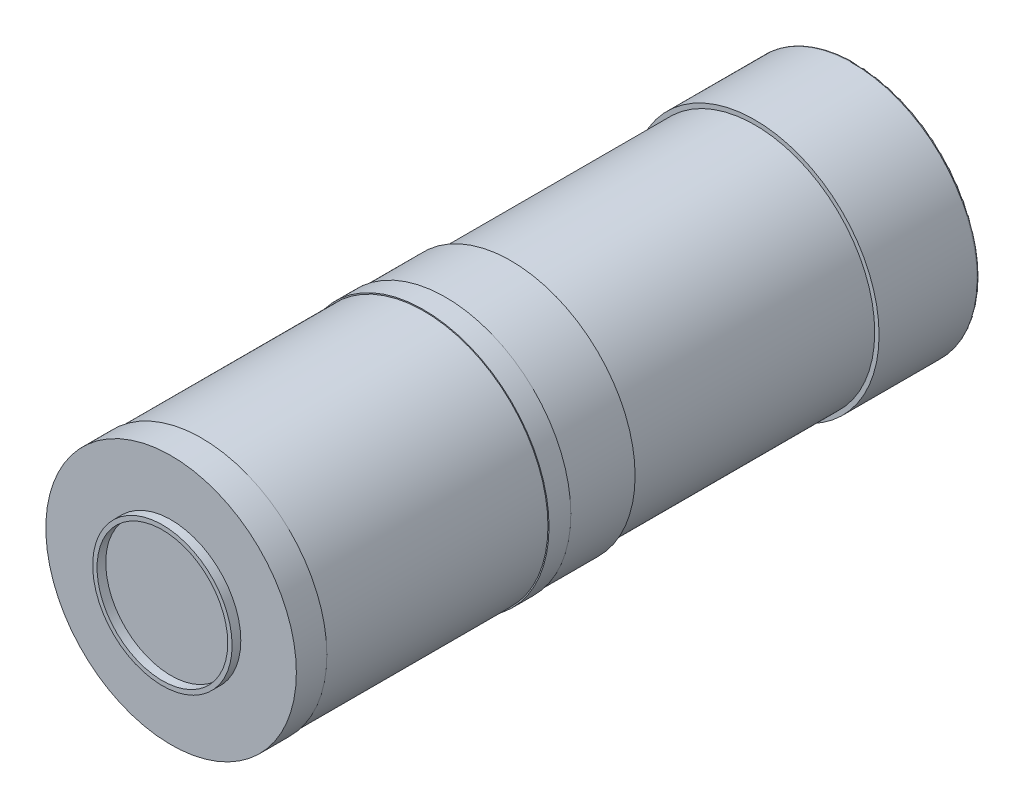
SolidWorks part; units mm, degrees
ref_plane "Plan de face" through (0, 0, 0) normal (0, 0, 1) x (1, 0, 0)
ref_plane "Plan de dessus" through (0, 0, 0) normal (0, 1, 0) x (1, 0, 0)
ref_plane "Plan de droite" through (0, 0, 0) normal (1, 0, 0) x (0, 0, -1)
sketch "Esquisse1" plane through (0, 0, 0) normal (0, 0, 1) x (1, 0, 0)
  circle A0 centre (0, 0) radius 28.5
  dimension "D1" = 57
extrude "Boss.-Extru.1" add sketch "Esquisse1" along normal blind 23
sketch "Esquisse3" plane through (0, 0, 23) normal (0, 0, 1) x (1, 0, 0)
  circle A0 centre (0, 0) radius 27.5
  dimension "D1" = 55
extrude "Boss.-Extru.2" add sketch "Esquisse3" along normal blind 56
sketch "Esquisse4" plane through (0, 0, 79) normal (0, 0, 1) x (1, 0, 0)
  circle A0 centre (0, 0) radius 28.5
  dimension "D1" = 57
extrude "Boss.-Extru.3" add sketch "Esquisse4" along normal blind 15
sketch "Esquisse5" plane through (0, 0, 94) normal (0, 0, 1) x (1, 0, 0)
  circle A0 centre (0, 0) radius 28.75
  dimension "D1" = 57.5
extrude "Boss.-Extru.4" add sketch "Esquisse5" along normal blind 5
sketch "Esquisse6" plane through (0, 0, 99) normal (0, 0, 1) x (1, 0, 0)
  circle A0 centre (0, 0) radius 28.5
  dimension "D1" = 57
extrude "Boss.-Extru.5" add sketch "Esquisse6" along normal blind 51
sketch "Esquisse7" plane through (0, 0, 150) normal (0, 0, 1) x (1, 0, 0)
  circle A0 centre (0, 0) radius 28.75
  circle A1 centre (0, 0) radius 28.75 construction
extrude "Boss.-Extru.6" add sketch "Esquisse7" along normal blind 7
fillet "Congé1" radius 0.5 1 edges at (28.5, 0, 0)
sketch "Esquisse8" plane through (0, 0, 157) normal (0, 0, 1) x (1, 0, 0)
  circle A0 centre (0, 0) radius 16
  circle A1 centre (0, 0) radius 15
  dimension "D1" = 32
  dimension "D2" = 1
extrude "Boss.-Extru.7" add sketch "Esquisse8" along normal blind 2
sketch "Esquisse9" plane through (0, 0, 157) normal (0, 0, 1) x (1, 0, 0)
  circle A0 centre (0, 0) radius 8.5
  dimension "D1" = 17
